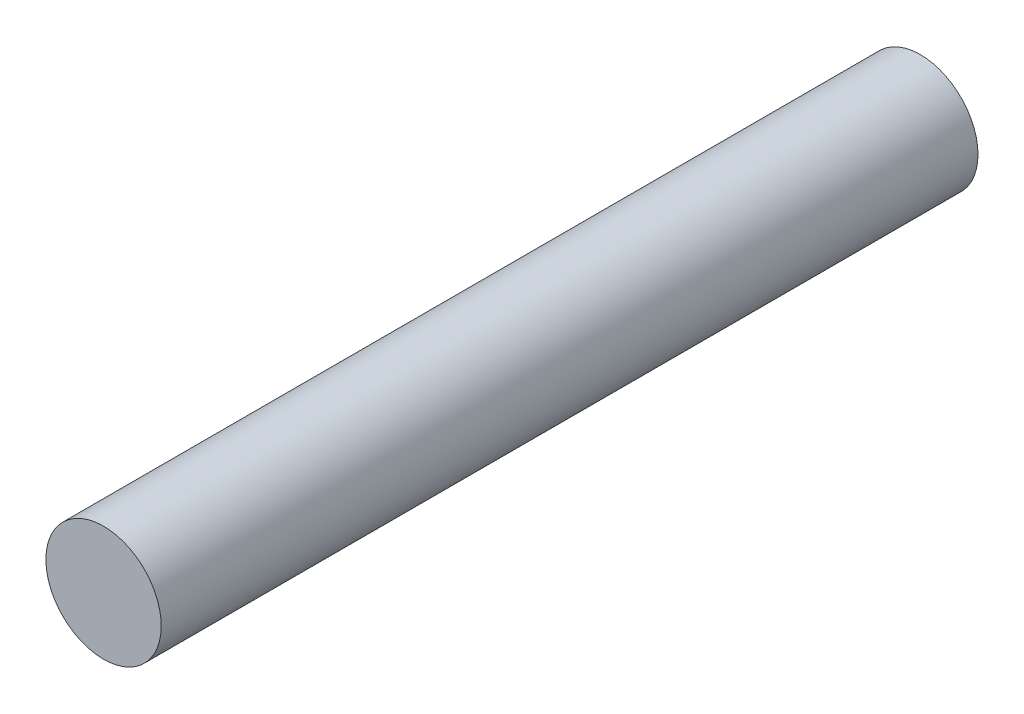
SolidWorks part; units mm, degrees
ref_plane "Front Plane" through (0, 0, 0) normal (0, 0, 1) x (1, 0, 0)
ref_plane "Top Plane" through (0, 0, 0) normal (0, 1, 0) x (1, 0, 0)
ref_plane "Right Plane" through (0, 0, 0) normal (1, 0, 0) x (0, 0, -1)
sketch "Sketch1" plane through (0, 0, 0) normal (0, 0, 1) x (1, 0, 0)
  circle A0 centre (0, 0) radius 6
extrude "Boss-Extrude1" add sketch "Sketch1" along normal blind 85
sketch "Sketch2" plane through (0, 0, 0) normal (0, 0, -1) x (-1, 0, 0)
  line L0 (0, 6) -> (0, -6) construction
  circle A0 centre (0, 0) radius 6 construction
  dimension "D1" = 12
